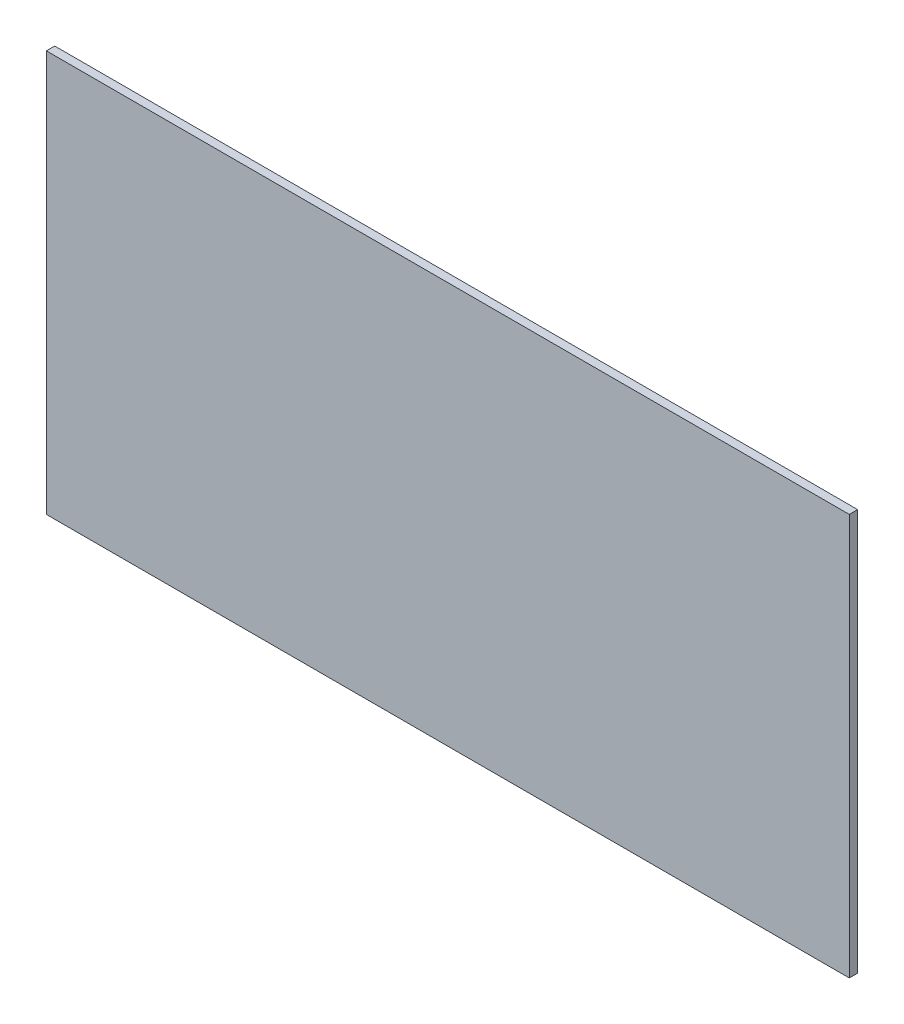
SolidWorks part; units mm, degrees
material "Pine"
ref_plane "Front Plane" through (0, 0, 0) normal (0, 0, 1) x (1, 0, 0)
ref_plane "Top Plane" through (0, 0, 0) normal (0, 1, 0) x (1, 0, 0)
ref_plane "Right Plane" through (0, 0, 0) normal (1, 0, 0) x (0, 0, -1)
sketch "Sketch1" plane through (0, 0, 0) normal (0, 0, 1) x (1, 0, 0)
  line L1 (0, 0) -> (1828.8, 0)
  line L2 (0, 0) -> (0, -914.4)
  line L3 (0, -914.4) -> (1828.8, -914.4)
  line L4 (1828.8, 0) -> (1828.8, -914.4)
  dimension "D1" = 1828.8
  dimension "D2" = 914.4
extrude "Boss-Extrude1" add sketch "Sketch1" along normal blind 19.05
equation "\"TableFrontWidth\"=64"
equation "\"TableSideWidth\"=28"
equation "\"LegWidth\"=3.5"
equation "\"LegHeight\"=32"
equation "\"LegDistToBottomStretcher\"=7"
equation "\"BottomStretcherLength\"=\"TableFrontWidth\""
equation "\"SideStretcherLength\"=\"TableSideWidth\"-3"
equation "\"BottomSupportLength\"=\"TableSideWidth\"-3"
equation "\"BottomPlywoodFrontDim\"=\"TableFrontWidth\"-\"LegWidth\"*2-3"
equation "\"BottomPlywoodSideDim\"=\"BottomSupportLength\""
equation "\"D2@Sketch1\"=\"TableSideWidth\"+\"OverhangSideDim\"+\"OverhangSideDim\""
equation "\"D1@Sketch1\"=\"TableFrontWidth\"+\"OverhangFrontDim\"+\"OverhangFrontDim\""
equation "\"TotalBottomSupports\"=4"
equation "\"TotalBottomSupportsLessOne\"=\"TotalBottomSupports\"-1"
equation "\"TotalTopSupports\"=5"
equation "\"TotalTopSupportsLessOne\"=\"TotalTopSupports\"-1"
equation "\"TopSupportSpread\"=\"TableFrontWidth\"-1.5"
equation "\"DistBetweenTopSupports\"=\"TopSupportSpread\"/\"TotalTopSupportsLessOne\""
equation "\"BottomSupportSpread\"= \"BottomPlywoodFrontDim\" - 1.5"
equation "\"DistBetweenBottomSupports\"=\"BottomSupportSpread\"/\"TotalBottomSupportsLessOne\""
equation "\"OverhangFrontDim\"=4"
equation "\"OverhangSideDim\"=4"
